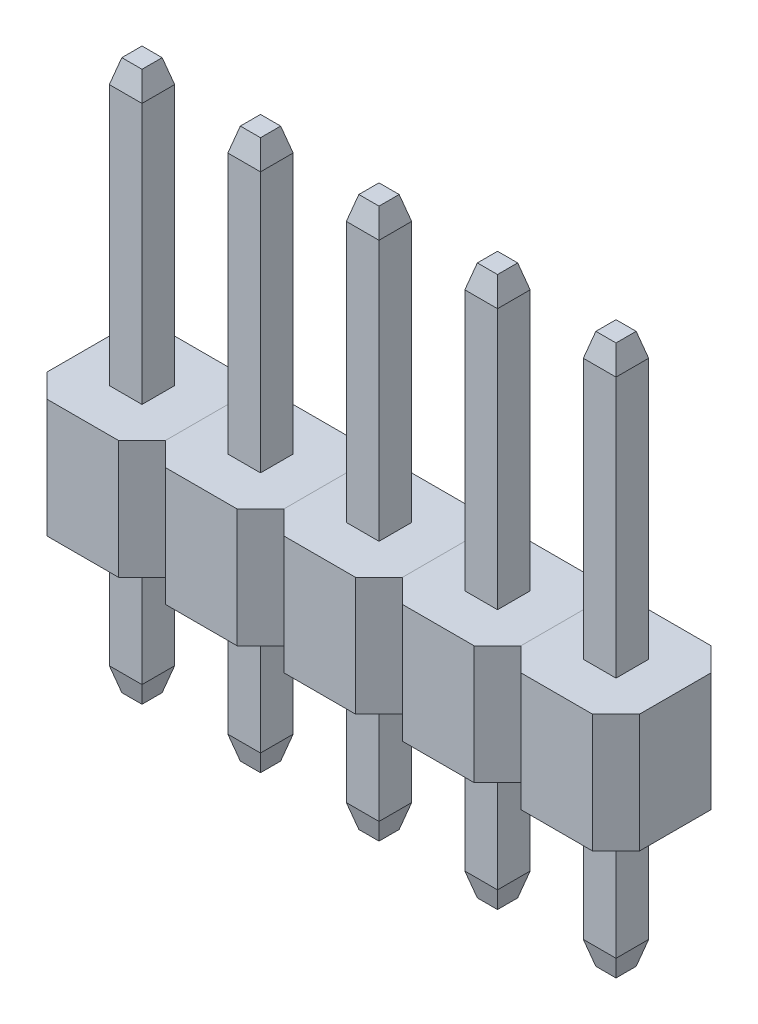
SolidWorks part; units mm, degrees
ref_plane "Front Plane" through (0, 0, 0) normal (0, 0, 1) x (1, 0, 0)
ref_plane "Top Plane" through (0, 0, 0) normal (0, 1, 0) x (1, 0, 0)
ref_plane "Right Plane" through (0, 0, 0) normal (1, 0, 0) x (0, 0, -1)
sketch "Sketch3" plane through (0, 0, 0) normal (0, 1, 0) x (1, 0, 0)
  line L1 (-1.27, 1.27) -> (1.27, 1.27)
  line L2 (-1.27, 1.27) -> (-1.27, -1.27)
  line L3 (-1.27, -1.27) -> (1.27, -1.27)
  line L4 (1.27, 1.27) -> (1.27, -1.27)
  line L5 (-1.27, 1.27) -> (1.27, -1.27) construction
  line L6 (-1.27, -1.27) -> (1.27, 1.27) construction
  line L7 (0.3175, -0.3175) -> (-0.3175, -0.3175)
  line L8 (0.3175, -0.3175) -> (0.3175, 0.3175)
  line L9 (0.3175, 0.3175) -> (-0.3175, 0.3175)
  line L10 (-0.3175, -0.3175) -> (-0.3175, 0.3175)
  line L11 (0.3175, -0.3175) -> (-0.3175, 0.3175) construction
  line L12 (0.3175, 0.3175) -> (-0.3175, -0.3175) construction
  point P0 (0, 0)
  point P7 (0, 0)
  dimension "D1" = 2.54
  dimension "D2" = 0.635
extrude "Boss-Extrude1" add sketch "Sketch3" along normal mid plane 2.54
chamfer "Chamfer1" distance 0.5 angle 45 4 edges at (-1.27, 0, 1.27) (-1.27, 0, -1.27) (1.27, 0, -1.27) (1.27, 0, 1.27)
sketch "Sketch5" plane through (0, 1.27, 0) normal (0, 1, 0) x (1, 0, 0)
  line L1 (0.35, -0.35) -> (-0.35, -0.35)
  line L2 (0.35, -0.35) -> (0.35, 0.35)
  line L3 (0.35, 0.35) -> (-0.35, 0.35)
  line L4 (-0.35, -0.35) -> (-0.35, 0.35)
  line L5 (0.35, -0.35) -> (-0.35, 0.35) construction
  line L6 (0.35, 0.35) -> (-0.35, -0.35) construction
  point P0 (0, 0)
  dimension "D1" = 0.7
extrude "Boss-Extrude2" add sketch "Sketch5" along normal blind 5.588 and the other way blind 5.2 separate body
sketch "Sketch6" plane through (0, 6.858, 0) normal (0, 1, 0) x (1, 0, 0)
  line L4 (-0.35, 0.35) -> (-0.35, -0.35)
  line L5 (-0.35, -0.35) -> (0.35, -0.35)
  line L6 (0.35, -0.35) -> (0.35, 0.35)
  line L7 (0.35, 0.35) -> (-0.35, 0.35)
  line L8 (-0.35, 0.35) -> (-0.35, -0.35)
  line L9 (-0.35, -0.35) -> (0.35, -0.35)
  line L10 (0.35, -0.35) -> (0.35, 0.35)
  line L11 (0.35, 0.35) -> (-0.35, 0.35)
  dimension "D1" = 0
extrude "Boss-Extrude3" add sketch "Sketch6" along normal blind 0.5 draft 15
sketch "Sketch7" plane through (0, -3.93, 0) normal (0, -1, 0) x (1, 0, 0)
  line L4 (-0.35, 0.35) -> (-0.35, -0.35)
  line L5 (-0.35, -0.35) -> (0.35, -0.35)
  line L6 (0.35, -0.35) -> (0.35, 0.35)
  line L7 (0.35, 0.35) -> (-0.35, 0.35)
  line L8 (-0.35, 0.35) -> (-0.35, -0.35)
  line L9 (-0.35, -0.35) -> (0.35, -0.35)
  line L10 (0.35, -0.35) -> (0.35, 0.35)
  line L11 (0.35, 0.35) -> (-0.35, 0.35)
  dimension "D1" = 0
extrude "Boss-Extrude4" add sketch "Sketch7" along normal blind 0.5 draft 15
pattern_linear "LPattern1" count 5 spacing 2.54 along (1, 0, 0) of "Boss-Extrude1", "Boss-Extrude2"
